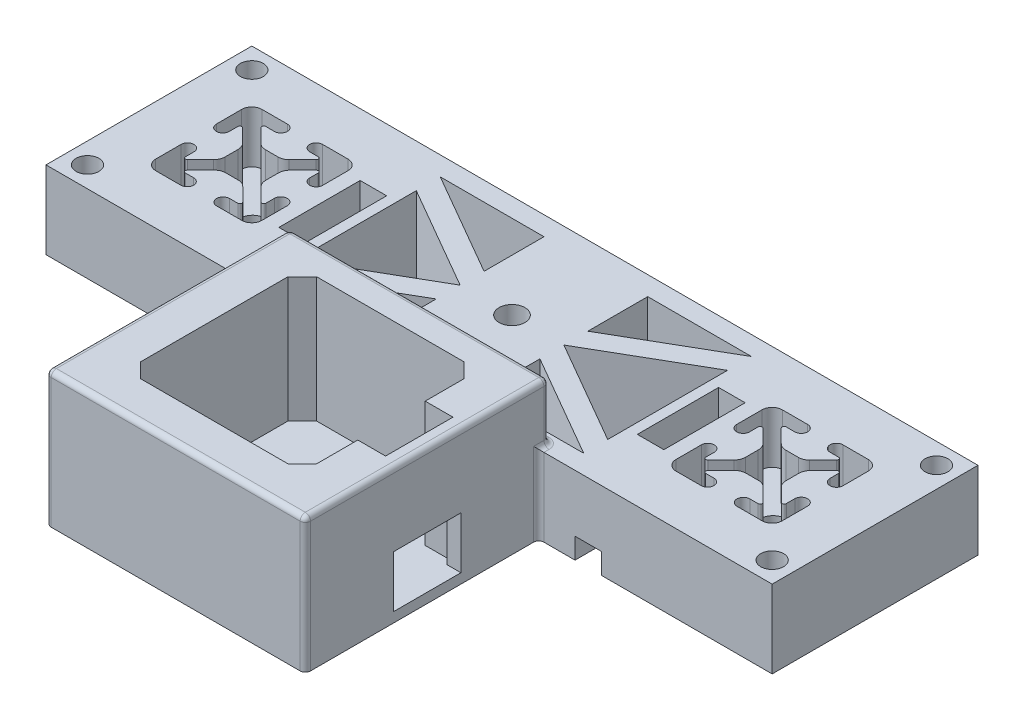
SolidWorks part; units mm, degrees
ref_plane "Front" through (0, 0, 0) normal (0, 0, 1) x (1, 0, 0)
ref_plane "Top" through (0, 0, 0) normal (0, 1, 0) x (1, 0, 0)
ref_plane "Right" through (0, 0, 0) normal (1, 0, 0) x (0, 0, -1)
sketch "Sketch1" plane through (0, 0, 0) normal (0, 1, 0) x (1, 0, 0)
  line L1 (0, 0) -> (177.8, 0)
  line L2 (0, 0) -> (0, 50.4)
  line L3 (0, 50.4) -> (177.8, 50.4)
  line L4 (177.8, 0) -> (177.8, 50.4)
  dimension "D1" = 177.8
  dimension "D2" = 50.4
extrude "Boss-Extrude1" add sketch "Sketch1" along normal blind 6.35
sketch "Sketch2" plane through (0, 6.35, 0) normal (0, 1, 0) x (1, 0, 0)
  line L0 (37.6996, 29.52) -> (37.6996, 35.7372) construction
  line L1 (35.7368, 37.7) -> (29.5196, 37.7) construction
  line L2 (29.5196, 35.56) -> (31.619, 35.56) construction
  line L3 (32.3326, 33.8353) -> (28.9966, 30.504) construction
  line L4 (26.7566, 29.5771) -> (23.643, 29.5771) construction
  line L5 (21.403, 30.504) -> (18.067, 33.8353) construction
  line L6 (18.7806, 35.56) -> (20.88, 35.56) construction
  line L7 (20.88, 37.7) -> (14.6628, 37.7) construction
  line L8 (12.7, 35.7372) -> (12.7, 29.52) construction
  line L9 (14.84, 29.52) -> (14.84, 31.5965) construction
  line L10 (16.5637, 32.3112) -> (19.7659, 29.1135) construction
  line L11 (20.743, 26.7568) -> (20.743, 23.6432) construction
  line L12 (19.7659, 21.2865) -> (16.5637, 18.0888) construction
  line L13 (14.84, 18.8035) -> (14.84, 20.88) construction
  line L14 (12.7, 20.88) -> (12.7, 14.6628) construction
  line L15 (14.6628, 12.7) -> (20.8121, 12.7) construction
  line L16 (20.8121, 14.84) -> (18.7806, 14.84) construction
  line L17 (18.067, 16.5647) -> (21.403, 19.896) construction
  line L18 (23.643, 20.8229) -> (26.7566, 20.8229) construction
  line L19 (28.9966, 19.896) -> (32.3326, 16.5647) construction
  line L20 (31.619, 14.84) -> (29.5875, 14.84) construction
  line L21 (29.5875, 12.7) -> (35.7368, 12.7) construction
  line L22 (37.6996, 14.6628) -> (37.6996, 20.88) construction
  line L23 (35.5596, 20.88) -> (35.5596, 18.8035) construction
  line L24 (33.8359, 18.0888) -> (30.6337, 21.2865) construction
  line L25 (29.6566, 23.6432) -> (29.6566, 26.7568) construction
  line L26 (30.6337, 29.1135) -> (33.8359, 32.3112) construction
  line L27 (35.5596, 31.5965) -> (35.5596, 29.52) construction
  line L28 (0, 50.4) -> (0, 0) construction
  line L29 (177.8, 50.4) -> (0, 50.4) construction
  line L30 (0, 0) -> (177.8, 0) construction
  line L31 (88.9, 50.4) -> (88.9, 0) construction
  line L32 (142.2404, 31.5965) -> (142.2404, 29.52) construction
  line L33 (147.1663, 29.1135) -> (143.9641, 32.3112) construction
  line L34 (148.1434, 23.6432) -> (148.1434, 26.7568) construction
  line L35 (143.9641, 18.0888) -> (147.1663, 21.2865) construction
  line L36 (142.2404, 20.88) -> (142.2404, 18.8035) construction
  line L37 (140.1004, 14.6628) -> (140.1004, 20.88) construction
  line L38 (148.2125, 12.7) -> (142.0632, 12.7) construction
  line L39 (146.181, 14.84) -> (148.2125, 14.84) construction
  line L40 (148.8034, 19.896) -> (145.4674, 16.5647) construction
  line L41 (154.157, 20.8229) -> (151.0434, 20.8229) construction
  line L42 (159.733, 16.5647) -> (156.397, 19.896) construction
  line L43 (156.9879, 14.84) -> (159.0194, 14.84) construction
  line L44 (163.1372, 12.7) -> (156.9879, 12.7) construction
  line L45 (165.1, 20.88) -> (165.1, 14.6628) construction
  line L46 (162.96, 18.8035) -> (162.96, 20.88) construction
  line L47 (158.0341, 21.2865) -> (161.2363, 18.0888) construction
  line L48 (157.057, 26.7568) -> (157.057, 23.6432) construction
  line L49 (161.2363, 32.3112) -> (158.0341, 29.1135) construction
  line L50 (162.96, 29.52) -> (162.96, 31.5965) construction
  line L51 (165.1, 35.7372) -> (165.1, 29.52) construction
  line L52 (156.92, 37.7) -> (163.1372, 37.7) construction
  line L53 (159.0194, 35.56) -> (156.92, 35.56) construction
  line L54 (156.397, 30.504) -> (159.733, 33.8353) construction
  line L55 (151.0434, 29.5771) -> (154.157, 29.5771) construction
  line L56 (145.4674, 33.8353) -> (148.8034, 30.504) construction
  line L57 (148.2804, 35.56) -> (146.181, 35.56) construction
  line L58 (142.0632, 37.7) -> (148.2804, 37.7) construction
  line L59 (140.1004, 29.52) -> (140.1004, 35.7372) construction
  line L60 (38.2076, 29.52) -> (38.2076, 35.7372)
  line L62 (0, 50.4) -> (0, 0)
  line L63 (0, 0) -> (177.8, 0)
  line L64 (177.8, 50.4) -> (177.8, 0)
  line L65 (35.7368, 38.208) -> (29.5196, 38.208)
  line L66 (29.5196, 35.052) -> (31.619, 35.052)
  line L67 (31.9737, 34.1948) -> (28.6376, 30.8635)
  line L68 (26.7566, 30.0851) -> (23.643, 30.0851)
  line L69 (21.762, 30.8635) -> (18.4259, 34.1948)
  line L70 (18.7806, 35.052) -> (20.88, 35.052)
  line L71 (20.88, 38.208) -> (14.6628, 38.208)
  line L72 (12.192, 35.7372) -> (12.192, 29.52)
  line L73 (15.348, 29.52) -> (15.348, 31.5965)
  line L74 (16.2047, 31.9517) -> (19.4069, 28.7541)
  line L75 (20.235, 26.7568) -> (20.235, 23.6432)
  line L76 (19.4069, 21.6459) -> (16.2047, 18.4483)
  line L77 (15.348, 18.8035) -> (15.348, 20.88)
  line L78 (12.192, 20.88) -> (12.192, 14.6628)
  line L79 (14.6628, 12.192) -> (20.8121, 12.192)
  line L80 (20.8121, 15.348) -> (18.7806, 15.348)
  line L81 (18.4259, 16.2052) -> (21.762, 19.5365)
  line L82 (23.643, 20.3149) -> (26.7566, 20.3149)
  line L83 (28.6376, 19.5365) -> (31.9737, 16.2052)
  line L84 (31.619, 15.348) -> (29.5875, 15.348)
  line L85 (29.5875, 12.192) -> (35.7368, 12.192)
  line L86 (38.2076, 14.6628) -> (38.2076, 20.88)
  line L87 (35.0516, 20.88) -> (35.0516, 18.8035)
  line L88 (34.1949, 18.4483) -> (30.9927, 21.6459)
  line L89 (30.1646, 23.6432) -> (30.1646, 26.7568)
  line L90 (30.9927, 28.7541) -> (34.1949, 31.9517)
  line L91 (35.0516, 31.5965) -> (35.0516, 29.52)
  line L92 (142.7484, 31.5965) -> (142.7484, 29.52)
  line L93 (139.5924, 29.52) -> (139.5924, 35.7372)
  line L94 (142.0632, 38.208) -> (148.2804, 38.208)
  line L95 (148.2804, 35.052) -> (146.181, 35.052)
  line L96 (145.8263, 34.1948) -> (149.1624, 30.8635)
  line L97 (151.0434, 30.0851) -> (154.157, 30.0851)
  line L98 (156.038, 30.8635) -> (159.3741, 34.1948)
  line L99 (159.0194, 35.052) -> (156.92, 35.052)
  line L100 (156.92, 38.208) -> (163.1372, 38.208)
  line L101 (165.608, 35.7372) -> (165.608, 29.52)
  line L102 (162.452, 29.52) -> (162.452, 31.5965)
  line L103 (161.5953, 31.9517) -> (158.3931, 28.7541)
  line L104 (157.565, 26.7568) -> (157.565, 23.6432)
  line L105 (158.3931, 21.6459) -> (161.5953, 18.4483)
  line L106 (162.452, 18.8035) -> (162.452, 20.88)
  line L107 (165.608, 20.88) -> (165.608, 14.6628)
  line L108 (163.1372, 12.192) -> (156.9879, 12.192)
  line L109 (156.9879, 15.348) -> (159.0194, 15.348)
  line L110 (159.3741, 16.2052) -> (156.038, 19.5365)
  line L111 (154.157, 20.3149) -> (151.0434, 20.3149)
  line L112 (149.1624, 19.5365) -> (145.8263, 16.2052)
  line L113 (146.181, 15.348) -> (148.2125, 15.348)
  line L114 (148.2125, 12.192) -> (142.0632, 12.192)
  line L115 (139.5924, 14.6628) -> (139.5924, 20.88)
  line L116 (142.7484, 20.88) -> (142.7484, 18.8035)
  line L117 (143.6051, 18.4483) -> (146.8073, 21.6459)
  line L118 (147.6354, 23.6432) -> (147.6354, 26.7568)
  line L119 (146.8073, 28.7541) -> (143.6051, 31.9517)
  line L120 (177.8, 50.4) -> (0, 50.4)
  arc A1 (37.6996, 35.7372) -> (35.7368, 37.7) centre (35.7368, 35.7372) ccw construction
  arc A2 (29.5196, 37.7) -> (29.5196, 35.56) centre (29.5196, 36.63) ccw construction
  arc A3 (31.619, 35.56) -> (32.3326, 33.8353) centre (31.619, 34.55) cw construction
  arc A4 (28.9966, 30.504) -> (26.7566, 29.5771) centre (26.7566, 32.7471) cw construction
  arc A5 (23.643, 29.5771) -> (21.403, 30.504) centre (23.643, 32.7471) cw construction
  arc A6 (18.067, 33.8353) -> (18.7806, 35.56) centre (18.7806, 34.55) cw construction
  arc A7 (20.88, 35.56) -> (20.88, 37.7) centre (20.88, 36.63) ccw construction
  arc A8 (14.6628, 37.7) -> (12.7, 35.7372) centre (14.6628, 35.7372) ccw construction
  arc A9 (12.7, 29.52) -> (14.84, 29.52) centre (13.77, 29.52) ccw construction
  arc A10 (14.84, 31.5965) -> (16.5637, 32.3112) centre (15.85, 31.5965) cw construction
  arc A11 (19.7659, 29.1135) -> (20.743, 26.7568) centre (17.4126, 26.7568) cw construction
  arc A12 (20.743, 23.6432) -> (19.7659, 21.2865) centre (17.4126, 23.6432) cw construction
  arc A13 (16.5637, 18.0888) -> (14.84, 18.8035) centre (15.85, 18.8035) cw construction
  arc A14 (14.84, 20.88) -> (12.7, 20.88) centre (13.77, 20.88) ccw construction
  arc A15 (12.7, 14.6628) -> (14.6628, 12.7) centre (14.6628, 14.6628) ccw construction
  arc A16 (20.8121, 12.7) -> (20.8121, 14.84) centre (20.8121, 13.77) ccw construction
  arc A17 (18.7806, 14.84) -> (18.067, 16.5647) centre (18.7806, 15.85) cw construction
  arc A18 (21.403, 19.896) -> (23.643, 20.8229) centre (23.643, 17.6529) cw construction
  arc A19 (26.7566, 20.8229) -> (28.9966, 19.896) centre (26.7566, 17.6529) cw construction
  arc A20 (32.3326, 16.5647) -> (31.619, 14.84) centre (31.619, 15.85) cw construction
  arc A21 (29.5875, 14.84) -> (29.5875, 12.7) centre (29.5875, 13.77) ccw construction
  arc A22 (35.7368, 12.7) -> (37.6996, 14.6628) centre (35.7368, 14.6628) ccw construction
  arc A23 (37.6996, 20.88) -> (35.5596, 20.88) centre (36.6296, 20.88) ccw construction
  arc A24 (35.5596, 18.8035) -> (33.8359, 18.0888) centre (34.5496, 18.8035) cw construction
  arc A25 (30.6337, 21.2865) -> (29.6566, 23.6432) centre (32.987, 23.6432) cw construction
  arc A26 (29.6566, 26.7568) -> (30.6337, 29.1135) centre (32.987, 26.7568) cw construction
  arc A27 (33.8359, 32.3112) -> (35.5596, 31.5965) centre (34.5496, 31.5965) cw construction
  arc A28 (35.5596, 29.52) -> (37.6996, 29.52) centre (36.6296, 29.52) ccw construction
  arc A29 (142.2404, 29.52) -> (140.1004, 29.52) centre (141.1704, 29.52) cw construction
  arc A30 (143.9641, 32.3112) -> (142.2404, 31.5965) centre (143.2504, 31.5965) ccw construction
  arc A31 (148.1434, 26.7568) -> (147.1663, 29.1135) centre (144.813, 26.7568) ccw construction
  arc A32 (147.1663, 21.2865) -> (148.1434, 23.6432) centre (144.813, 23.6432) ccw construction
  arc A33 (142.2404, 18.8035) -> (143.9641, 18.0888) centre (143.2504, 18.8035) ccw construction
  arc A34 (140.1004, 20.88) -> (142.2404, 20.88) centre (141.1704, 20.88) cw construction
  arc A35 (142.0632, 12.7) -> (140.1004, 14.6628) centre (142.0632, 14.6628) cw construction
  arc A36 (148.2125, 14.84) -> (148.2125, 12.7) centre (148.2125, 13.77) cw construction
  arc A37 (145.4674, 16.5647) -> (146.181, 14.84) centre (146.181, 15.85) ccw construction
  arc A38 (151.0434, 20.8229) -> (148.8034, 19.896) centre (151.0434, 17.6529) ccw construction
  arc A39 (156.397, 19.896) -> (154.157, 20.8229) centre (154.157, 17.6529) ccw construction
  arc A40 (159.0194, 14.84) -> (159.733, 16.5647) centre (159.0194, 15.85) ccw construction
  arc A41 (156.9879, 12.7) -> (156.9879, 14.84) centre (156.9879, 13.77) cw construction
  arc A42 (165.1, 14.6628) -> (163.1372, 12.7) centre (163.1372, 14.6628) cw construction
  arc A43 (162.96, 20.88) -> (165.1, 20.88) centre (164.03, 20.88) cw construction
  arc A44 (161.2363, 18.0888) -> (162.96, 18.8035) centre (161.95, 18.8035) ccw construction
  arc A45 (157.057, 23.6432) -> (158.0341, 21.2865) centre (160.3874, 23.6432) ccw construction
  arc A46 (158.0341, 29.1135) -> (157.057, 26.7568) centre (160.3874, 26.7568) ccw construction
  arc A47 (162.96, 31.5965) -> (161.2363, 32.3112) centre (161.95, 31.5965) ccw construction
  arc A48 (165.1, 29.52) -> (162.96, 29.52) centre (164.03, 29.52) cw construction
  arc A49 (163.1372, 37.7) -> (165.1, 35.7372) centre (163.1372, 35.7372) cw construction
  arc A50 (156.92, 35.56) -> (156.92, 37.7) centre (156.92, 36.63) cw construction
  arc A51 (159.733, 33.8353) -> (159.0194, 35.56) centre (159.0194, 34.55) ccw construction
  arc A52 (154.157, 29.5771) -> (156.397, 30.504) centre (154.157, 32.7471) ccw construction
  arc A53 (148.8034, 30.504) -> (151.0434, 29.5771) centre (151.0434, 32.7471) ccw construction
  arc A54 (146.181, 35.56) -> (145.4674, 33.8353) centre (146.181, 34.55) ccw construction
  arc A55 (148.2804, 37.7) -> (148.2804, 35.56) centre (148.2804, 36.63) cw construction
  arc A56 (140.1004, 35.7372) -> (142.0632, 37.7) centre (142.0632, 35.7372) cw construction
  arc A58 (38.2076, 35.7372) -> (35.7368, 38.208) centre (35.7368, 35.7372) ccw
  arc A59 (29.5196, 38.208) -> (29.5196, 35.052) centre (29.5196, 36.63) ccw
  arc A60 (31.619, 35.052) -> (31.9737, 34.1948) centre (31.619, 34.55) cw
  arc A61 (28.6376, 30.8635) -> (26.7566, 30.0851) centre (26.7566, 32.7471) cw
  arc A62 (23.643, 30.0851) -> (21.762, 30.8635) centre (23.643, 32.7471) cw
  arc A63 (18.4259, 34.1948) -> (18.7806, 35.052) centre (18.7806, 34.55) cw
  arc A64 (20.88, 35.052) -> (20.88, 38.208) centre (20.88, 36.63) ccw
  arc A65 (14.6628, 38.208) -> (12.192, 35.7372) centre (14.6628, 35.7372) ccw
  arc A66 (12.192, 29.52) -> (15.348, 29.52) centre (13.77, 29.52) ccw
  arc A67 (15.348, 31.5965) -> (16.2047, 31.9517) centre (15.85, 31.5965) cw
  arc A68 (19.4069, 28.7541) -> (20.235, 26.7568) centre (17.4126, 26.7568) cw
  arc A69 (20.235, 23.6432) -> (19.4069, 21.6459) centre (17.4126, 23.6432) cw
  arc A70 (16.2047, 18.4483) -> (15.348, 18.8035) centre (15.85, 18.8035) cw
  arc A71 (15.348, 20.88) -> (12.192, 20.88) centre (13.77, 20.88) ccw
  arc A72 (12.192, 14.6628) -> (14.6628, 12.192) centre (14.6628, 14.6628) ccw
  arc A73 (20.8121, 12.192) -> (20.8121, 15.348) centre (20.8121, 13.77) ccw
  arc A74 (18.7806, 15.348) -> (18.4259, 16.2052) centre (18.7806, 15.85) cw
  arc A75 (21.762, 19.5365) -> (23.643, 20.3149) centre (23.643, 17.6529) cw
  arc A76 (26.7566, 20.3149) -> (28.6376, 19.5365) centre (26.7566, 17.6529) cw
  arc A77 (31.9737, 16.2052) -> (31.619, 15.348) centre (31.619, 15.85) cw
  arc A78 (29.5875, 15.348) -> (29.5875, 12.192) centre (29.5875, 13.77) ccw
  arc A79 (35.7368, 12.192) -> (38.2076, 14.6628) centre (35.7368, 14.6628) ccw
  arc A80 (38.2076, 20.88) -> (35.0516, 20.88) centre (36.6296, 20.88) ccw
  arc A81 (35.0516, 18.8035) -> (34.1949, 18.4483) centre (34.5496, 18.8035) cw
  arc A82 (30.9927, 21.6459) -> (30.1646, 23.6432) centre (32.987, 23.6432) cw
  arc A83 (30.1646, 26.7568) -> (30.9927, 28.7541) centre (32.987, 26.7568) cw
  arc A84 (34.1949, 31.9517) -> (35.0516, 31.5965) centre (34.5496, 31.5965) cw
  arc A85 (35.0516, 29.52) -> (38.2076, 29.52) centre (36.6296, 29.52) ccw
  arc A86 (142.7484, 29.52) -> (139.5924, 29.52) centre (141.1704, 29.52) cw
  arc A87 (139.5924, 35.7372) -> (142.0632, 38.208) centre (142.0632, 35.7372) cw
  arc A88 (148.2804, 38.208) -> (148.2804, 35.052) centre (148.2804, 36.63) cw
  arc A89 (146.181, 35.052) -> (145.8263, 34.1948) centre (146.181, 34.55) ccw
  arc A90 (149.1624, 30.8635) -> (151.0434, 30.0851) centre (151.0434, 32.7471) ccw
  arc A91 (154.157, 30.0851) -> (156.038, 30.8635) centre (154.157, 32.7471) ccw
  arc A92 (159.3741, 34.1948) -> (159.0194, 35.052) centre (159.0194, 34.55) ccw
  arc A93 (156.92, 35.052) -> (156.92, 38.208) centre (156.92, 36.63) cw
  arc A94 (163.1372, 38.208) -> (165.608, 35.7372) centre (163.1372, 35.7372) cw
  arc A95 (165.608, 29.52) -> (162.452, 29.52) centre (164.03, 29.52) cw
  arc A96 (162.452, 31.5965) -> (161.5953, 31.9517) centre (161.95, 31.5965) ccw
  arc A97 (158.3931, 28.7541) -> (157.565, 26.7568) centre (160.3874, 26.7568) ccw
  arc A98 (157.565, 23.6432) -> (158.3931, 21.6459) centre (160.3874, 23.6432) ccw
  arc A99 (161.5953, 18.4483) -> (162.452, 18.8035) centre (161.95, 18.8035) ccw
  arc A100 (162.452, 20.88) -> (165.608, 20.88) centre (164.03, 20.88) cw
  arc A101 (165.608, 14.6628) -> (163.1372, 12.192) centre (163.1372, 14.6628) cw
  arc A102 (156.9879, 12.192) -> (156.9879, 15.348) centre (156.9879, 13.77) cw
  arc A103 (159.0194, 15.348) -> (159.3741, 16.2052) centre (159.0194, 15.85) ccw
  arc A104 (156.038, 19.5365) -> (154.157, 20.3149) centre (154.157, 17.6529) ccw
  arc A105 (151.0434, 20.3149) -> (149.1624, 19.5365) centre (151.0434, 17.6529) ccw
  arc A106 (145.8263, 16.2052) -> (146.181, 15.348) centre (146.181, 15.85) ccw
  arc A107 (148.2125, 15.348) -> (148.2125, 12.192) centre (148.2125, 13.77) cw
  arc A108 (142.0632, 12.192) -> (139.5924, 14.6628) centre (142.0632, 14.6628) cw
  arc A109 (139.5924, 20.88) -> (142.7484, 20.88) centre (141.1704, 20.88) cw
  arc A110 (142.7484, 18.8035) -> (143.6051, 18.4483) centre (143.2504, 18.8035) ccw
  arc A111 (146.8073, 21.6459) -> (147.6354, 23.6432) centre (144.813, 23.6432) ccw
  arc A112 (147.6354, 26.7568) -> (146.8073, 28.7541) centre (144.813, 26.7568) ccw
  arc A113 (143.6051, 31.9517) -> (142.7484, 31.5965) centre (143.2504, 31.5965) ccw
  dimension "D2" = 1.07
  dimension "D3" = 3.17
  dimension "D4" = 3.3305
  dimension "D8" = 1.9628
  dimension "D9" = 1.01
  dimension "D5" = 12.7
  dimension "D6" = 12.7
  dimension "D7" = 12.7
  dimension "D10" = 16.5637
  dimension "D12" = 0.508
  dimension "D13" = 0.508
extrude "Boss-Extrude2" add sketch "Sketch2" along normal blind 12.7
sketch "Sketch3" plane through (0, 19.05, 0) normal (0, 1, 0) x (1, 0, 0)
  line L0 (177.8, 50.4) -> (0, 50.4) construction
  line L1 (0, 50.4) -> (0, 0) construction
  circle A0 centre (88.9, 25.2) radius 3.175
  point P4 (88.9, 50.4)
  point P7 (0, 25.2)
  dimension "D1" = 6.35
extrude "Cut-Extrude1" cut sketch "Sketch3" against normal through all
sketch "Sketch4" plane through (0, 19.05, 0) normal (0, 1, 0) x (1, 0, 0)
  line L0 (50.8, 45.7306) -> (76.2, 45.7306)
  line L1 (76.2, 45.7306) -> (76.2, 31.0659)
  line L2 (76.2, 31.0659) -> (50.8, 45.7306)
  line L3 (76.2, 19.3341) -> (76.2, 4.6694)
  line L4 (76.2, 4.6694) -> (50.8, 4.6694)
  line L5 (50.8, 4.6694) -> (76.2, 19.3341)
  line L6 (50.8, 39.8647) -> (50.8, 10.5353)
  line L7 (50.8, 10.5353) -> (76.2, 25.2)
  line L8 (76.2, 25.2) -> (50.8, 39.8647)
  line L9 (0, 50.4) -> (0, 0) construction
  line L10 (88.9, 50.4) -> (88.9, 0) construction
  line L11 (177.8, 50.4) -> (0, 50.4) construction
  line L12 (0, 0) -> (177.8, 0) construction
  line L13 (101.6, 25.2) -> (127, 39.8647)
  line L14 (127, 10.5353) -> (101.6, 25.2)
  line L15 (127, 39.8647) -> (127, 10.5353)
  line L16 (127, 4.6694) -> (101.6, 19.3341)
  line L17 (101.6, 4.6694) -> (127, 4.6694)
  line L18 (101.6, 19.3341) -> (101.6, 4.6694)
  line L19 (101.6, 31.0659) -> (127, 45.7306)
  line L20 (101.6, 45.7306) -> (101.6, 31.0659)
  line L21 (127, 45.7306) -> (101.6, 45.7306)
  point P18 (88.9, 25.2)
  dimension "D1" = 25.4
  dimension "D2" = 25.4
  dimension "D3" = 50.8
  dimension "D4" = 5.08
  dimension "D5" = 5.08
  dimension "D7" = 60
extrude "Cut-Extrude2" cut sketch "Sketch4" against normal through all
sketch "Sketch5" plane through (0, 19.05, 0) normal (0, 1, 0) x (1, 0, 0)
  line L0 (0, 50.4) -> (0, 0) construction
  line L1 (41.7636, 35.15) -> (48.2636, 35.15)
  line L2 (41.7636, 35.15) -> (41.7636, 15.25)
  line L3 (41.7636, 15.25) -> (48.2636, 15.25)
  line L4 (48.2636, 35.15) -> (48.2636, 15.25)
  line L5 (38.2076, 29.52) -> (38.2076, 35.7372) construction
  point P6 (0, 25.2)
  point P7 (48.2636, 25.2)
  dimension "D1" = 6.5
  dimension "D2" = 19.9
  dimension "D3" = 3.556
extrude "Cut-Extrude3" cut sketch "Sketch5" against normal blind 10.2
sketch "Sketch6" plane through (0, 8.85, 0) normal (0, 1, 0) x (1, 0, 0)
  line L0 (48.2636, 15.25) -> (48.2636, 35.15) construction
  line L1 (41.7636, 35.15) -> (48.2636, 35.15)
  line L2 (41.7636, 35.15) -> (41.7636, 30.578)
  line L3 (41.7636, 30.578) -> (48.2636, 30.578)
  line L4 (48.2636, 35.15) -> (48.2636, 30.578)
  line L5 (41.7636, 35.15) -> (41.7636, 15.25) construction
  line L6 (48.2636, 15.25) -> (48.2636, 35.15) construction
  line L7 (41.7636, 27.486) -> (48.2636, 27.486)
  line L8 (41.7636, 27.486) -> (41.7636, 22.914)
  line L9 (41.7636, 22.914) -> (48.2636, 22.914)
  line L10 (48.2636, 27.486) -> (48.2636, 22.914)
  line L12 (41.7636, 15.25) -> (48.2636, 15.25)
  line L13 (41.7636, 15.25) -> (41.7636, 19.822)
  line L14 (41.7636, 19.822) -> (48.2636, 19.822)
  line L15 (48.2636, 15.25) -> (48.2636, 19.822)
  line L16 (41.7636, 25.2) -> (0, 25.2) construction
  line L17 (0, 50.4) -> (0, 0) construction
  dimension "D1" = 4.572
extrude "Cut-Extrude4" cut sketch "Sketch6" against normal through all
ref_plane "Plane1" through (88.9, 0, 0) normal (-1, 0, 0) x (0, 0, 1)
mirror "Mirror1" about plane through (88.9, 0, 0) normal (-1, 0, 0) of "Cut-Extrude4", "Cut-Extrude3"
sketch "Sketch7" plane through (0, 6.35, 0) normal (0, 1, 0) x (1, 0, 0)
  line L0 (26.7566, 30.0851) -> (23.643, 30.0851) construction
  line L1 (30.1646, 23.6432) -> (30.1646, 26.7568) construction
  circle A0 centre (25.3386, 25.2591) radius 2.921
  dimension "D1" = 5.842
  dimension "D2" = 4.826
  dimension "D3" = 4.826
extrude "Cut-Extrude5" cut sketch "Sketch7" against normal through all both and the other way through all
sketch "Sketch8" plane through (0, 6.35, 0) normal (0, 1, 0) x (1, 0, 0)
  line L0 (154.157, 30.0851) -> (151.0434, 30.0851) construction
  line L1 (157.565, 23.6432) -> (157.565, 26.7568) construction
  circle A0 centre (152.739, 25.2591) radius 2.921
  dimension "D1" = 5.842
  dimension "D2" = 4.826
  dimension "D3" = 4.826
extrude "Cut-Extrude6" cut sketch "Sketch8" against normal through all both and the other way through all
chamfer "Chamfer2" distance 3.302 angle 45 1 edges at (152.739, 0, -22.3381)
chamfer "Chamfer3" distance 3.302 angle 45 1 edges at (25.3386, 0, -22.3381)
sketch "Sketch9" plane through (0, 0, 0) normal (0, 1, 0) x (1, 0, 0)
  line L0 (120.65, 0) -> (120.65, -57.15)
  line L3 (0, 0) -> (177.8, 0) construction
  line L8 (57.15, -57.15) -> (120.65, -57.15)
  line L13 (57.15, 0) -> (57.15, -57.15)
  line L15 (57.15, 0) -> (57.15, 2.54)
  line L16 (57.15, 2.54) -> (120.65, 2.54)
  line L17 (120.65, 0) -> (120.65, 2.54)
  dimension "D1" = 57.15
  dimension "D2" = 63.5
  dimension "D3" = 2.54
sketch "Sketch11" plane through (0, 0, 0) normal (0, 1, 0) x (1, 0, 0)
  line L0 (0, 0) -> (177.8, 0) construction
  line L2 (41.7636, 15.25) -> (41.7636, 0)
  line L3 (41.7636, 0) -> (48.2636, 0)
  line L4 (48.2636, 15.25) -> (48.2636, 0)
  line L5 (48.2636, 15.25) -> (48.2636, 35.15) construction
  line L6 (177.8, 50.4) -> (0, 50.4) construction
  line L8 (41.7636, 35.15) -> (41.7636, 50.4)
  line L9 (41.7636, 50.4) -> (48.2636, 50.4)
  line L10 (48.2636, 35.15) -> (48.2636, 50.4)
  line L11 (41.7636, 35.15) -> (41.7636, 15.25)
  line L12 (48.2636, 35.15) -> (48.2636, 15.25)
  line L13 (88.9, 50.4) -> (88.9, 0) construction
  line L14 (136.0364, 0) -> (129.5364, 0)
  line L15 (136.0364, 50.4) -> (129.5364, 50.4)
  line L16 (129.5364, 15.25) -> (129.5364, 0)
  line L17 (136.0364, 15.25) -> (136.0364, 0)
  line L18 (129.5364, 35.15) -> (129.5364, 15.25)
  line L19 (136.0364, 35.15) -> (136.0364, 15.25)
  line L20 (129.5364, 35.15) -> (129.5364, 50.4)
  line L21 (136.0364, 35.15) -> (136.0364, 50.4)
extrude "Cut-Extrude8" cut sketch "Sketch11" along normal blind 5.08
extrude "Boss-Extrude4" add sketch "Sketch9" along normal blind 33.02
sketch "Sketch12" plane through (0, 33.02, 0) normal (0, 1, 0) x (1, 0, 0)
  line L0 (70.8455, -4.556) -> (106.9545, -4.556)
  line L1 (106.9545, -4.556) -> (110.49, -8.0915)
  line L2 (110.49, -8.0915) -> (110.49, -17.642)
  line L3 (110.49, -44.2005) -> (106.9545, -47.736)
  line L4 (106.9545, -47.736) -> (70.8455, -47.736)
  line L5 (70.8455, -47.736) -> (67.31, -44.2005)
  line L6 (67.31, -44.2005) -> (67.31, -8.0915)
  line L7 (67.31, -8.0915) -> (70.8455, -4.556)
  line L8 (57.15, -57.15) -> (120.65, -57.15) construction
  line L9 (85.725, 25.2) -> (92.075, 25.2) construction
  line L10 (110.49, -34.142) -> (110.49, -44.2005)
  line L11 (110.49, -17.642) -> (117.29, -17.642)
  line L13 (110.49, -34.142) -> (117.29, -34.142)
  line L14 (117.29, -17.642) -> (117.29, -34.142)
  line L16 (57.15, 2.54) -> (120.65, 2.54) construction
  circle A0 centre (88.9, 25.2) radius 3.175 construction
  point P10 (88.9, -57.15)
  point P11 (88.9, -47.736)
  point P15 (67.31, -26.146)
  dimension "D9" = 28.686
  dimension "D1" = 5
  dimension "D2" = 43.18
  dimension "D3" = 135
  dimension "D4" = 135
  dimension "D5" = 135
  dimension "D6" = 43.18
  dimension "D7" = 16.5
  dimension "D8" = 6.8
extrude "Cut-Extrude9" cut sketch "Sketch12" against normal blind 30.6
sketch "Sketch13" plane through (120.65, 0, 0) normal (1, 0, 0) x (0, 0, -1)
  line L0 (-57.15, 33.02) -> (2.54, 33.02) construction
  line L1 (-35.555, 15.12) -> (-19.055, 15.12)
  line L2 (-35.555, 15.12) -> (-35.555, 2.42)
  line L3 (-35.555, 2.42) -> (-19.055, 2.42)
  line L4 (-19.055, 15.12) -> (-19.055, 2.42)
  point P6 (-27.305, 33.02)
  point P7 (-27.305, 15.12)
  dimension "D1" = 16.5
  dimension "D2" = 12.7
  dimension "D3" = 30.6
extrude "Cut-Extrude10" cut sketch "Sketch13" against normal blind 30.6
fillet "Fillet1" radius 1.27 13 edges at (120.65, 19.05, -1.27) (57.15, 19.05, -1.27) (120.65, 26.035, -2.54) (57.15, 26.035, -2.54) (88.9, 19.05, -2.54) (57.15, 9.525, 0) (120.65, 9.525, 0) (120.65, 33.02, 27.305) (120.65, 16.51, 57.15) (88.9, 33.02, 57.15) (57.15, 33.02, 27.305) (57.15, 16.51, 57.15) (88.9, 33.02, -2.54)
sketch "Sketch14" plane through (0, 2.42, 0) normal (0, 1, 0) x (1, 0, 0)
  line L0 (88.9, -4.556) -> (88.9, -47.736) construction
  line L1 (106.9545, -4.556) -> (70.8455, -4.556) construction
  line L2 (70.8455, -47.736) -> (106.9545, -47.736) construction
  circle A0 centre (88.9, -26.146) radius 2.921
  dimension "D1" = 5.842
extrude "Cut-Extrude11" cut sketch "Sketch14" against normal through all
sketch "Sketch15" plane through (0, 0, 0) normal (0, 1, 0) x (1, 0, 0)
  circle A0 centre (88.9, 25.2) radius 10.16
  dimension "D1" = 20.32
extrude "Cut-Extrude12" cut sketch "Sketch15" along normal blind 8.128
sketch "Sketch16" plane through (0, 19.05, 0) normal (0, 1, 0) x (1, 0, 0)
  line L0 (88.9, 50.4) -> (88.9, -47.736) construction
  line L1 (177.8, 50.4) -> (0, 50.4) construction
  line L2 (70.8455, -47.736) -> (106.9545, -47.736) construction
  line L3 (0, 25.2) -> (177.8, 25.2) construction
  line L4 (0, 50.4) -> (0, 0) construction
  line L5 (177.8, 0) -> (177.8, 50.4) construction
  circle A0 centre (5.08, 45.32) radius 2.794
  circle A1 centre (5.08, 5.08) radius 2.794
  circle A2 centre (172.72, 5.08) radius 2.794
  circle A3 centre (172.72, 45.32) radius 2.794
  dimension "D1" = 5.588
  dimension "D3" = 5.08
  dimension "D2" = 5.08
extrude "Cut-Extrude13" cut sketch "Sketch16" against normal through all
